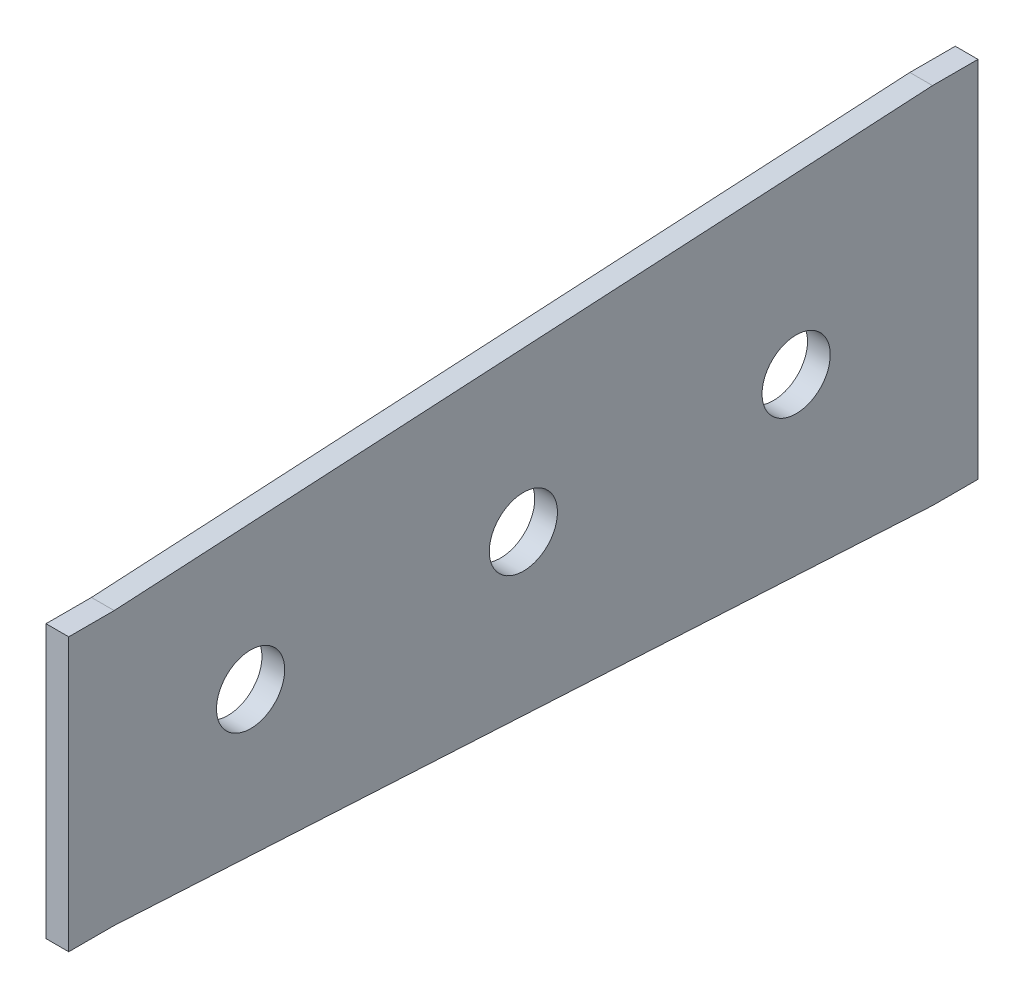
SolidWorks part; units mm, degrees
ref_plane "Front Plane" through (0, 0, 0) normal (0, 0, 1) x (1, 0, 0)
ref_plane "Top Plane" through (0, 0, 0) normal (0, 1, 0) x (1, 0, 0)
ref_plane "Right Plane" through (0, 0, 0) normal (1, 0, 0) x (0, 0, -1)
sketch "Sketch1" plane through (0, 0, 0) normal (1, 0, 0) x (0, 0, -1)
  line L0 (-60, 0) -> (60, 0) construction
  line L1 (100, -40) -> (100, 40)
  line L2 (-100, 30) -> (-100, -30)
  line L5 (-100, 30) -> (-90, 30)
  line L7 (-100, -30) -> (-90, -30)
  line L9 (-100, 0) -> (100, 0) construction
  line L10 (100, 40) -> (90, 40)
  line L11 (90, 40) -> (-90, 30)
  line L12 (100, -40) -> (90, -40)
  line L13 (90, -40) -> (-90, -30)
  circle A0 centre (0, 0) radius 7.5
  circle A1 centre (-60, 0) radius 7.5
  circle A2 centre (60, 0) radius 7.5
  point P10 (0, 0)
  point P13 (-100, 0)
  point P16 (100, 0)
  dimension "D1" = 15
  dimension "D3" = 200
  dimension "D2" = 120
  dimension "D5" = 80
  dimension "D6" = 60
  dimension "D7" = 10
extrude "Boss-Extrude1" add sketch "Sketch1" along normal mid plane 5
